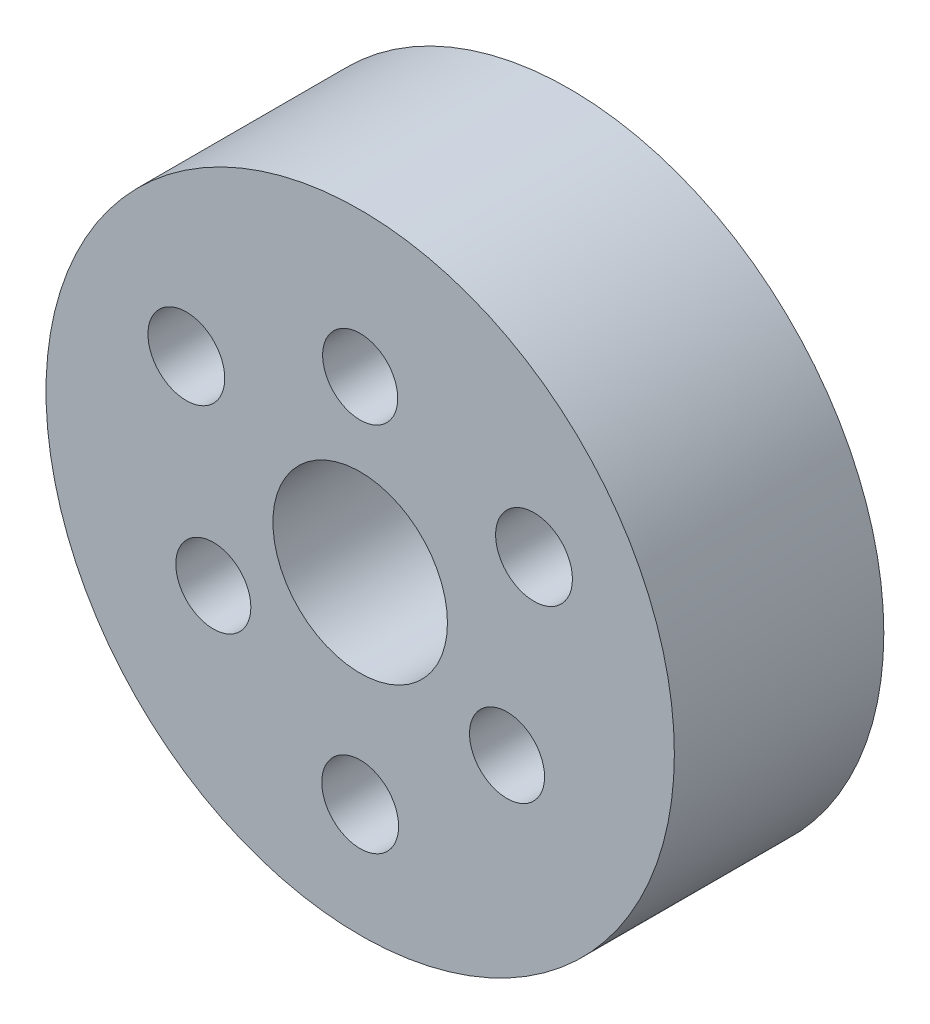
SolidWorks part; units mm, degrees
material "PLA"
ref_plane "前视基准面" through (0, 0, 0) normal (0, 0, 1) x (1, 0, 0)
ref_plane "上视基准面" through (0, 0, 0) normal (0, 1, 0) x (1, 0, 0)
ref_plane "右视基准面" through (0, 0, 0) normal (1, 0, 0) x (0, 0, -1)
sketch "草图1" plane through (0, 0, 0) normal (0, 0, 1) x (1, 0, 0)
  circle A0 centre (0, 0) radius 18
  dimension "D1" = 36
extrude "凸台-拉伸1" add sketch "草图1" along normal blind 12
sketch "草图3" plane through (0, 0, 12) normal (0, 0, 1) x (1, 0, 0)
  line L0 (9.9593, 5.75) -> (0, 0) construction
  line L1 (0, 0) -> (0, 9.715) construction
  circle A0 centre (0, 0) radius 11.5 construction
  circle A1 centre (0, 0) radius 9.715 construction
  circle A2 centre (0, 9.715) radius 2.15
  circle A3 centre (8.4134, -4.8575) radius 2.15
  circle A4 centre (-8.4134, -4.8575) radius 2.15
  circle A5 centre (9.9593, 5.75) radius 2.2
  circle A6 centre (0, -11.5) radius 2.2
  circle A7 centre (-9.9593, 5.75) radius 2.2
  point P6 (-12.339, 6.1184)
  point P7 (0, 0)
  point P8 (0, 0)
  point P13 (0, 0)
  point P20 (0, 0)
  point P21 (0, 0)
  dimension "D1" = 23
  dimension "D2" = 19.43
  dimension "D3" = 4.3
  dimension "D5" = 4.4
  dimension "D6" = 60
  dimension "D4" = 3
  dimension "D7" = 3
extrude "切除-拉伸1" cut sketch "草图3" against normal through all
sketch "草图4" plane through (0, 0, 12) normal (0, 0, 1) x (1, 0, 0)
  circle A0 centre (0, 0) radius 5
  dimension "D1" = 10
extrude "切除-拉伸2" cut sketch "草图4" against normal through all
